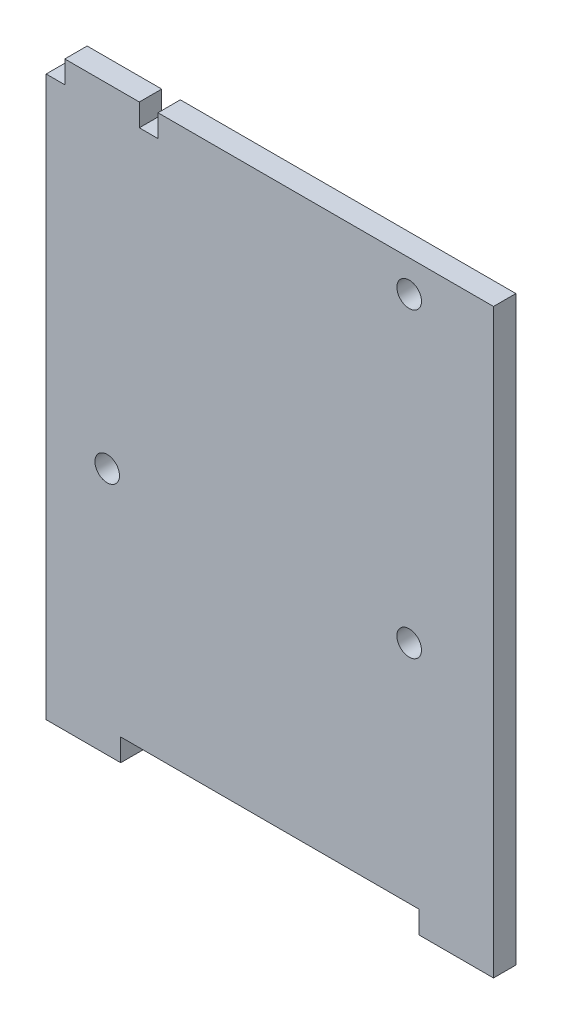
SolidWorks part; units mm, degrees
material "Acrylic (Medium-high impact)"
ref_plane "Front Plane" through (0, 0, 0) normal (0, 0, 1) x (1, 0, 0)
ref_plane "Top Plane" through (0, 0, 0) normal (0, 1, 0) x (1, 0, 0)
ref_plane "Right Plane" through (0, 0, 0) normal (1, 0, 0) x (0, 0, -1)
sketch "Sketch1" plane through (0, 0, 0) normal (0, 0, 1) x (1, 0, 0)
  line L1 (20, 0) -> (80, 0)
  line L2 (20, 0) -> (20, 75)
  line L3 (20, 75) -> (80, 75)
  line L4 (80, 0) -> (80, 75)
  dimension "D1" = 20
  dimension "D2" = 75
  dimension "D3" = 60
extrude "MainBody" add sketch "Sketch1" along normal mid plane 3
sketch "ShaftLayout" plane through (0, 0, 0) normal (0, 0, 1) x (1, 0, 0)
  line L0 (0, 20) -> (28.1908, 30.2606) construction
  line L1 (55, 0) -> (-55, 0) construction
  line L2 (28.1908, 30.2606) -> (68.6908, 30.2606) construction
  line L3 (68.6908, 30.2606) -> (68.6908, 70.7606) construction
  circle A0 centre (68.6908, 70.7606) radius 1.65
  circle A1 centre (68.6908, 30.2606) radius 1.65
  circle A2 centre (28.1908, 30.2606) radius 1.65
  point P0 (0, 20)
  dimension "D8" = 3.3
  dimension "D9" = 3.3
  dimension "D10" = 3.3
  dimension "D1" = 20
  dimension "D2" = 30
  dimension "D3" = 20
  dimension "D4" = 40.5
  dimension "D5" = 40.5
  dimension "D6" = 160
  dimension "D7" = 90
sketch "Sketch3" plane through (0, 0, 0) normal (0, 0, 1) x (1, 0, 0)
  circle A0 centre (68.6908, 70.7606) radius 1.65 construction
  circle A1 centre (68.6908, 30.2606) radius 1.65 construction
  circle A2 centre (28.1908, 30.2606) radius 1.65 construction
  circle A3 centre (28.1908, 30.2606) radius 1.65
  circle A4 centre (68.6908, 30.2606) radius 1.65
  circle A5 centre (68.6908, 70.7606) radius 1.65
extrude "Shaft Holes" cut sketch "Sketch3" against normal through all both and the other way through all
sketch "Sketch4" plane through (0, 0, 0) normal (0, 0, 1) x (1, 0, 0)
  line L1 (20, 0) -> (30, 0)
  line L2 (20, 0) -> (20, -3)
  line L3 (20, -3) -> (30, -3)
  line L4 (30, 0) -> (30, -3)
  line L5 (80, 0) -> (70, 0)
  line L6 (80, 0) -> (80, -3)
  line L7 (80, -3) -> (70, -3)
  line L8 (70, 0) -> (70, -3)
  dimension "D1" = 3
  dimension "D2" = 3
  dimension "D3" = 10
  dimension "D4" = 10
extrude "BaseTabs" add sketch "Sketch4" along normal mid plane 3
sketch "Sketch5" plane through (0, 0, 1.5) normal (0, 0, 1) x (1, 0, 0)
  line L0 (80, 75) -> (20, 75) construction
  line L1 (20, 75) -> (22.5, 75)
  line L2 (20, 75) -> (20, 72)
  line L3 (20, 72) -> (22.5, 72)
  line L4 (22.5, 75) -> (22.5, 72)
  line L5 (32.5, 75) -> (35, 75)
  line L6 (32.5, 75) -> (32.5, 72)
  line L7 (32.5, 72) -> (35, 72)
  line L8 (35, 75) -> (35, 72)
  dimension "D1" = 2.5
  dimension "D2" = 10
  dimension "D3" = 2.5
  dimension "D4" = 3
  dimension "D5" = 3
extrude "Cut-Extrude2" cut sketch "Sketch5" against normal through all
sketch "Sketch8" plane through (0, 0, 1.5) normal (0, 0, 1) x (1, 0, 0)
  line L0 (20, 39) -> (32, 39) construction
  line L1 (20, 72) -> (20, -3) construction
  line L2 (60.8802, 75) -> (60.8802, 65) construction
  line L3 (80, 75) -> (35, 75) construction
  line L4 (32.5, 75) -> (22.5, 75) construction
  line L5 (80, -3) -> (80, 75) construction
  arc A0 (32, 39) -> (60.8802, 65) centre (43.2676, 55.524) ccw construction
  arc A1 (30.3099, 36.5214) -> (63.5221, 66.4214) centre (43.2676, 55.524) ccw
  arc A2 (33.6901, 41.4786) -> (58.2383, 63.5786) centre (43.2676, 55.524) ccw
  arc A3 (33.6901, 41.4786) -> (30.3099, 36.5214) centre (32, 39) ccw
  arc A4 (63.5221, 66.4214) -> (58.2383, 63.5786) centre (60.8802, 65) ccw
  point P10 (56.6491, 40.6601)
  dimension "D1" = 3
  dimension "D4" = 20
  dimension "D2" = 36
  dimension "D3" = 12
  dimension "D5" = 10
  dimension "D6" = 19.1198
extrude "Cut-Extrude3" [suppressed] cut sketch "Sketch8" against normal blind 10
sketch "Sketch6" plane through (0, 0, 0) normal (0, 0, 1) x (1, 0, 0)
  line L120 (19.8558, -3.1442) -> (30.1442, -3.1442)
  line L121 (30.1442, -3.1442) -> (30.1442, -0.1442)
  line L122 (30.1442, -0.1442) -> (69.8558, -0.1442)
  line L123 (69.8558, -0.1442) -> (69.8558, -3.1442)
  line L124 (69.8558, -3.1442) -> (80.1442, -3.1442)
  line L125 (80.1442, -3.1442) -> (80.1442, 75.1442)
  line L126 (80.1442, 75.1442) -> (34.8558, 75.1442)
  line L127 (34.8558, 75.1442) -> (34.8558, 72.1442)
  line L128 (34.8558, 72.1442) -> (32.6442, 72.1442)
  line L129 (32.6442, 72.1442) -> (32.6442, 75.1442)
  line L130 (32.6442, 75.1442) -> (22.3558, 75.1442)
  line L131 (22.3558, 75.1442) -> (22.3558, 72.1442)
  line L132 (22.3558, 72.1442) -> (19.8558, 72.1442)
  line L133 (19.8558, 72.1442) -> (19.8558, -3.1442)
  line L134 (19.8558, -3.1442) -> (30.1442, -3.1442)
  line L135 (30.1442, -3.1442) -> (30.1442, -0.1442)
  line L136 (30.1442, -0.1442) -> (69.8558, -0.1442)
  line L137 (69.8558, -0.1442) -> (69.8558, -3.1442)
  line L138 (69.8558, -3.1442) -> (80.1442, -3.1442)
  line L139 (80.1442, -3.1442) -> (80.1442, 75.1442)
  line L140 (80.1442, 75.1442) -> (34.8558, 75.1442)
  line L141 (34.8558, 75.1442) -> (34.8558, 72.1442)
  line L142 (34.8558, 72.1442) -> (32.6442, 72.1442)
  line L143 (32.6442, 72.1442) -> (32.6442, 75.1442)
  line L144 (32.6442, 75.1442) -> (22.3558, 75.1442)
  line L145 (22.3558, 75.1442) -> (22.3558, 72.1442)
  line L146 (22.3558, 72.1442) -> (19.8558, 72.1442)
  line L147 (19.8558, 72.1442) -> (19.8558, -3.1442)
  circle A10 centre (28.1908, 30.2606) radius 1.5058
  circle A11 centre (28.1908, 30.2606) radius 1.5058
  circle A13 centre (68.6908, 30.2606) radius 1.5058
  circle A14 centre (68.6908, 30.2606) radius 1.5058
  circle A16 centre (68.6908, 70.7606) radius 1.5058
  circle A17 centre (68.6908, 70.7606) radius 1.5058
  arc A20 (33.609, 41.3596) -> (30.391, 36.6404) centre (32, 39) ccw
  arc A21 (33.609, 41.3596) -> (58.3651, 63.6468) centre (43.2676, 55.524) ccw
  arc A22 (63.3953, 66.3532) -> (58.3651, 63.6468) centre (60.8802, 65) ccw
  arc A23 (30.391, 36.6404) -> (63.3953, 66.3532) centre (43.2676, 55.524) ccw
  arc A24 (33.609, 41.3596) -> (30.391, 36.6404) centre (32, 39) ccw
  arc A25 (33.609, 41.3596) -> (58.3651, 63.6468) centre (43.2676, 55.524) ccw
  arc A26 (63.3953, 66.3532) -> (58.3651, 63.6468) centre (60.8802, 65) ccw
  arc A27 (30.391, 36.6404) -> (63.3953, 66.3532) centre (43.2676, 55.524) ccw
  dimension "D1" = 0.1442
  dimension "D2" = 0.1442
  dimension "D3" = 0.1442
  dimension "D4" = 0.1442
  dimension "D5" = 0.144
extrude "FOR the LASER CUTTER" [suppressed] add sketch "Sketch6" along normal mid plane 3
equation "\"D9@ShaftLayout\"=\"D8@ShaftLayout\""
equation "\"D10@ShaftLayout\"=\"D8@ShaftLayout\""
equation "\"D2@Sketch4\"=\"D1@Sketch4\""
